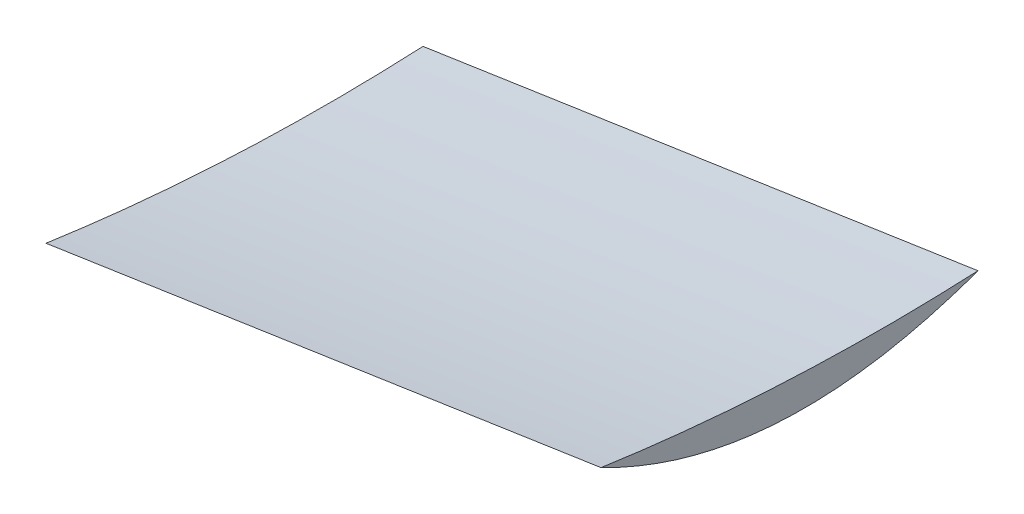
SolidWorks part; units mm, degrees
ref_plane "Front Plane" through (0, 0, 0) normal (0, 0, 1) x (1, 0, 0)
ref_plane "Top Plane" through (0, 0, 0) normal (0, 1, 0) x (1, 0, 0)
ref_plane "Right Plane" through (0, 0, 0) normal (1, 0, 0) x (0, 0, -1)
sketch "Sketch1" plane through (0, 0, 0) normal (1, 0, 0) x (0, 0, -1)
  spline S0 degree 2 poles (-44.9917, 21.7249) (207.2658, -14.7484) (462.4299, -2.5087) knots 0 0 0 1 1 1
  spline S1 degree 2 poles (-44.9917, 21.7249) (192.7329, -100.1016) (462.4299, -2.5087) knots 0 0 0 1 1 1
  point P0 (-44.9917, 21.7249)
  point P1 (462.4299, -2.5087)
  dimension "D2" = 50.8
  dimension "D1" = 508
sketch "Sketch2" plane through (0, 0, 0) normal (0, 1, 0) x (1, 0, 0)
  line L0 (0, 157.4919) -> (-635, 45.5243)
  line L1 (0, -44.9917) -> (0, 462.4299) construction
  line L2 (0, 157.4919) -> (0, -13.3335) construction
  dimension "D1" = 635
  dimension "D2" = 80
sweep "Sweep1" add profiles "Sketch1" path "Sketch2"
